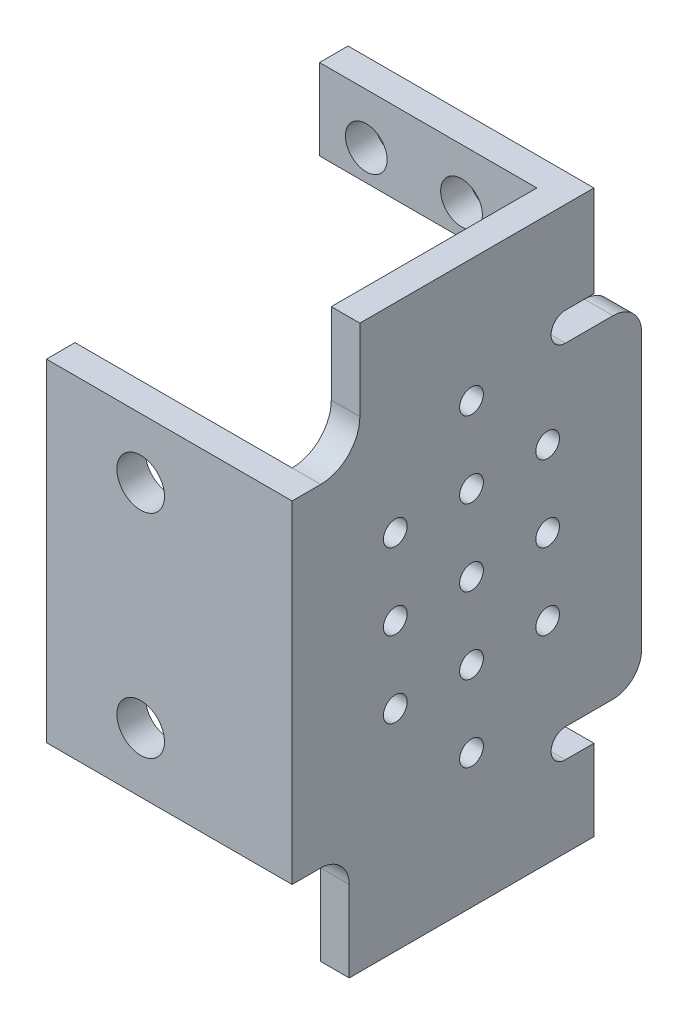
SolidWorks part; units mm, degrees
ref_plane "Plan de face" through (0, 0, 0) normal (0, 0, 1) x (1, 0, 0)
ref_plane "Plan de dessus" through (0, 0, 0) normal (0, 1, 0) x (1, 0, 0)
ref_plane "Plan de droite" through (0, 0, 0) normal (1, 0, 0) x (0, 0, -1)
sketch "Esquisse1" plane through (0, 0, 0) normal (0, 0, 1) x (1, 0, 0)
  line L0 (-22.1347, 3.0313) -> (-2.3147, 3.0313) construction
  line L1 (-17.2247, -41.6687) -> (-7.2247, -41.6687) construction
  line L2 (-17.2247, -41.6687) -> (-17.2247, 6.7313) construction
  line L3 (-17.2247, 6.7313) -> (-7.2247, 6.7313) construction
  line L4 (-7.2247, -41.6687) -> (-7.2247, 6.7313) construction
  line L5 (-17.2247, -41.6687) -> (-7.2247, 6.7313) construction
  line L6 (-17.2247, 6.7313) -> (-7.2247, -41.6687) construction
  line L7 (-22.1347, -37.9687) -> (-2.3147, -37.9687) construction
  line L8 (-22.1347, -37.9687) -> (-22.1347, 3.0313) construction
  line L9 (-22.1347, 3.0313) -> (-2.3147, 3.0313) construction
  line L10 (-2.3147, -37.9687) -> (-2.3147, 3.0313) construction
  line L11 (-22.1347, -37.9687) -> (-2.3147, 3.0313) construction
  line L12 (-22.1347, 3.0313) -> (-2.3147, -37.9687) construction
  line L13 (-22.1347, 3.0313) -> (-22.1347, 12.0313)
  line L14 (-2.3147, 3.0313) -> (-2.3147, 12.0313)
  line L15 (-22.1347, 12.0313) -> (-2.3147, 12.0313)
  line L16 (-22.1347, 3.5313) -> (-2.3147, 3.5313)
  line L17 (-22.1347, -37.9687) -> (-2.3147, -37.9687)
  line L18 (-22.1347, -37.9687) -> (-22.1347, -46.9687)
  line L19 (-2.3147, -37.9687) -> (-2.3147, -46.9687)
  line L20 (-22.1347, -46.9687) -> (-2.3147, -46.9687)
  line L21 (-22.1347, -38.4687) -> (-2.3147, -38.4687)
  line L22 (0.6853, 12.0313) -> (0.6853, -46.9687) construction
  line L23 (-2.3147, 12.0313) -> (0.6853, 12.0313)
  line L24 (-2.3147, 12.0313) -> (-2.3147, 2.4169)
  line L25 (0.6853, 12.0313) -> (0.6853, 2.4169)
  line L26 (-2.3147, 2.4169) -> (0.6853, 2.4169)
  line L27 (-2.3147, -46.9687) -> (0.6853, -46.9687)
  line L28 (-2.3147, -46.9687) -> (-2.3147, -38.4687)
  line L29 (0.6853, -46.9687) -> (0.6853, -38.4687)
  line L30 (-2.3147, -38.4687) -> (0.6853, -38.4687)
  circle A0 centre (-7.2247, 6.7313) radius 2.19
  circle A1 centre (-17.2247, 6.7313) radius 2.19
  circle A2 centre (-7.2247, -41.6687) radius 2.19
  circle A3 centre (-17.2247, -41.6687) radius 2.19
  point P0 (-12.2247, -17.4687)
  point P9 (-12.2247, -17.4687)
  dimension "D3" = 4.38
  dimension "D1" = 10
  dimension "D2" = 48.4
  dimension "D4" = 41
  dimension "D5" = 19.82
  dimension "D6" = 0.5
  dimension "D7" = 0.5
  dimension "D8" = 9
  dimension "D9" = 3
extrude "Boss.-Extru.2" add sketch "Esquisse1" along normal blind 3 contours L14 L26 L25 L23 | L30 L19 L27 L29 | L21 L18 L20 L19 A3 A2 | L13 L16 L14 L15 A1 A0
sketch "Esquisse3" plane through (0.6853, 0, 0) normal (1, 0, 0) x (0, 0, -1)
  line L0 (-3, -46.9687) -> (0, -46.9687) construction
  line L1 (0, 12.0313) -> (-31.7, 12.0313)
  line L2 (0, 12.0313) -> (0, -46.9687)
  line L3 (0, -46.9687) -> (-31.7, -46.9687)
  line L4 (-31.7, 12.0313) -> (-31.7, -46.9687)
  line L6 (0, 2.4169) -> (-3, 2.4169)
  line L7 (0, 2.4169) -> (0, -0.5831)
  line L8 (0, -0.5831) -> (-3, -0.5831)
  line L9 (-3, 2.4169) -> (-3, -0.5831)
  line L10 (0, -38.4687) -> (-3, -38.4687)
  line L11 (0, -38.4687) -> (0, -35.4687)
  line L12 (0, -35.4687) -> (-3, -35.4687)
  line L13 (-3, -38.4687) -> (-3, -35.4687)
  line L14 (0, -0.5831) -> (5, -0.5831)
  line L15 (0, -0.5831) -> (0, -35.4687)
  line L16 (0, -35.4687) -> (5, -35.4687)
  line L17 (5, -0.5831) -> (5, -35.4687)
  arc A0 (-3, 2.4169) -> (-3, -0.5831) centre (-3, 0.9169) ccw
  arc A1 (-3, -35.4687) -> (-3, -38.4687) centre (-3, -36.9687) ccw
  line M1 (0, 2.4169) -> (0, 12.0313)
  line M2 (0, 12.0313) -> (-3, 12.0313)
  line M3 (-3, 12.0313) -> (-3, 2.4169)
  line M4 (-3, 2.4169) -> (0, 2.4169)
  dimension "D1" = 31.7
  dimension "D2" = 5
extrude "Boss.-Extru.4" add sketch "Esquisse3" along normal blind 3 contours L10 L13 L12 L2 L8 L9 L1 L4 L3 M3 | L17 L14 L2 L16 | M4 M1 M2 M3
fillet "Congé1" radius 3 2 edges at (2.1853, -0.5831, -5) (2.1853, -35.4687, -5)
sketch "Esquisse4" plane through (3.6853, 0, 0) normal (1, 0, 0) x (0, 0, -1)
  line L1 (0, 12.0313) -> (-3, 12.0313)
  line L2 (0, 12.0313) -> (0, 2.4169)
  line L3 (0, 2.4169) -> (-3, 2.4169)
  line L4 (-3, 12.0313) -> (-3, 2.4169)
extrude "Boss.-Extru.5" add sketch "Esquisse4" against normal blind 5
sketch "Esquisse13" plane through (0.6853, 0, 0) normal (-1, 0, 0) x (0, 0, 1)
  line L0 (0.5, -0.5831) -> (31.7, -0.5831) construction
  line L2 (-2, -0.5831) -> (3, -0.5831) construction
  line L3 (31.7, 12.0313) -> (31.7, -46.9687) construction
  line L4 (3, 3.5313) -> (31.7, 3.5313) construction
  line L5 (-2, -35.4687) -> (31.7, -35.4687) construction
  line L7 (3, -38.4687) -> (31.7, -38.4687) construction
  line L8 (31.7, -0.5831) -> (31.7, -35.4687)
  line L9 (31.7, -0.5831) -> (28.7, -0.5831)
  line L10 (31.7, -35.4687) -> (28.7, -35.4687)
  line L11 (28.7, -0.5831) -> (28.7, -35.4687)
  line L12 (28.7, -35.4687) -> (28.7, -46.9687) construction
  line L14 (3, -46.9687) -> (31.7, -46.9687) construction
  line L15 (25.7, -38.4687) -> (25.7, -46.9687)
  line L16 (28.7, -35.4687) -> (25.7, -35.4687)
  line L17 (28.7, -35.4687) -> (28.7, -38.4687)
  line L18 (28.7, -38.4687) -> (25.7, -38.4687)
  line L19 (25.7, -35.4687) -> (25.7, -38.4687)
  line L20 (28.7, -0.5831) -> (24.5856, -0.5831)
  line L21 (28.7, -0.5831) -> (28.7, 3.5313)
  line L22 (28.7, 3.5313) -> (24.5856, 3.5313)
  line L23 (24.5856, -0.5831) -> (24.5856, 3.5313)
  line L24 (24.5856, 3.5313) -> (24.5856, 12.0313)
  line L25 (3, 12.0313) -> (31.7, 12.0313) construction
  arc A0 (28.7, -0.5831) -> (24.5856, 3.5313) centre (28.7, 3.5313) cw
  arc A1 (25.7, -38.4687) -> (28.7, -35.4687) centre (28.7, -38.4687) cw
  line M10 (3, -46.9687) -> (31.7, -46.9687)
  line M11 (31.7, -46.9687) -> (31.7, 12.0313)
  line M12 (31.7, 12.0313) -> (3, 12.0313)
  dimension "D1" = 3
extrude "Enlèv. mat.-Extru.1" cut sketch "Esquisse13" against normal blind 5 contours L24 L22 L21 L9 M11 M12 | A0 L21 L22 | L17 L18 L15 L10 M10 M11 | A1 L18 L17
sketch "Esquisse15" plane through (0.6853, 0, 0) normal (-1, 0, 0) x (0, 0, 1)
  line L0 (31.7, -0.5831) -> (31.7, -35.4687)
  line L1 (31.7, -0.5831) -> (28.7, -0.5831)
  line L2 (31.7, -35.4687) -> (28.7, -35.4687)
  line L3 (28.7, -0.5831) -> (28.7, -35.4687)
  dimension "D1" = 3
extrude "Boss.-Extru.6" add sketch "Esquisse15" along normal blind 22.8
sketch "Esquisse17" plane through (3.6853, 0, 0) normal (1, 0, 0) x (0, 0, -1)
  line L0 (-12.8616, -16.8909) -> (-31.7116, -16.8909) construction
  line L1 (-24.5856, 12.0313) -> (-0.0176, 12.0313)
  line L2 (-24.5856, 12.0313) -> (-24.5856, 1.4313)
  line L3 (-24.5856, 1.4313) -> (-0.0176, 1.4313)
  line L4 (-0.0176, 12.0313) -> (-0.0176, 1.4313)
  line L5 (-0.0176, 1.4313) -> (-25.7056, -35.2131) construction
  line L6 (-0.0056, -45.8131) -> (-25.7056, -45.8131) construction
  line L7 (-0.0056, -45.8131) -> (-0.0056, -35.2131) construction
  line L8 (-0.0056, -35.2131) -> (-25.7056, -35.2131) construction
  line L9 (-25.7056, -45.8131) -> (-25.7056, -35.2131) construction
  line L10 (-0.0056, -35.2131) -> (-24.5856, 1.4313) construction
  line L11 (-31.7, -0.5831) -> (-31.7, -35.4687) construction
  line L12 (-12.8616, -16.8759) -> (-12.8616, 1.4613) construction
  line L13 (-20.8616, -16.8909) -> (-20.8616, -8.8909) construction
  line L14 (-4.8616, -16.8909) -> (-4.8616, -8.2594) construction
  circle A0 centre (-12.8616, -16.8909) radius 8 construction
  circle A1 centre (-20.8616, -16.8909) radius 1.25
  circle A2 centre (-12.8616, -16.8909) radius 1.25
  circle A3 centre (-12.8616, -8.8909) radius 1.25
  circle A4 centre (-4.8616, -16.8909) radius 1.25
  circle A5 centre (-12.8616, -24.8909) radius 1.25
  circle A6 centre (-12.8616, -8.8909) radius 8 construction
  circle A7 centre (-12.8616, -24.8909) radius 8 construction
  circle A8 centre (-20.8616, -8.8909) radius 1.25
  circle A9 centre (-4.8616, -8.8909) radius 1.25
  circle A10 centre (-4.8616, -24.8909) radius 1.25
  circle A11 centre (-20.8616, -24.8909) radius 1.25
  circle A12 centre (-12.8616, -0.8909) radius 1.25
  circle A13 centre (-12.8616, -32.8909) radius 1.25
  dimension "D2" = 2.5
  dimension "D3" = 16
  dimension "D1" = 10.6
sketch "Esquisse18" plane through (3.6853, 0, 0) normal (1, 0, 0) x (0, 0, -1)
extrude "Enlèv. mat.-Extru.2" cut sketch "Esquisse17" against normal blind 4 contours A1 | A11 | A5 | A10 | A4 | A9 | A3 | A8 | A12 | A13 | A2
sketch "Esquisse19" plane through (0, 0, 31.7) normal (0, 0, 1) x (1, 0, 0)
  line L0 (-12.2147, -18.0259) -> (-12.2147, -7.7531) construction
  line L2 (3.6853, -0.5831) -> (-22.1147, -0.5831) construction
  line L3 (3.6853, -3.5831) -> (3.6853, -32.4687) construction
  line L4 (-19.0136, -6.8731) -> (-5.4158, -6.8731) construction
  line L5 (-19.0136, -6.8731) -> (-19.0136, -29.1787) construction
  line L6 (-19.0136, -29.1787) -> (-5.4158, -29.1787) construction
  line L7 (3.6853, -34.3187) -> (0.6853, -34.3187)
  line L8 (3.6853, -34.3187) -> (3.6853, -0.5831)
  line L9 (3.6853, -0.5831) -> (0.6853, -0.5831)
  line L10 (0.6853, -34.3187) -> (0.6853, -0.5831)
  line L11 (-5.4158, -6.8731) -> (-5.4158, -29.1787) construction
  line L13 (-12.2997, -18.0259) -> (-23.6997, -18.0259) construction
  line L14 (-22.1147, -35.4687) -> (-22.1147, -0.5831) construction
  circle A0 centre (-12.2147, -6.8731) radius 2.5
  circle A1 centre (-12.2147, -29.1787) radius 2.5
  circle A2 centre (-12.2147, -18.0259) radius 11.1528 construction
  point P12 (-12.2147, -6.8731)
  point P13 (-12.2147, -29.1787)
  point P22 (-19.0136, -18.0259)
  point P23 (-12.2147, -29.1787)
  point P25 (-22.1147, -18.0259)
  dimension "D1" = 6.29
  dimension "D2" = 5
  dimension "D4" = 9.9
  dimension "D3" = 3
extrude "Enlèv. mat.-Extru.5" cut sketch "Esquisse19" against normal blind 4 contours A0 | A1
